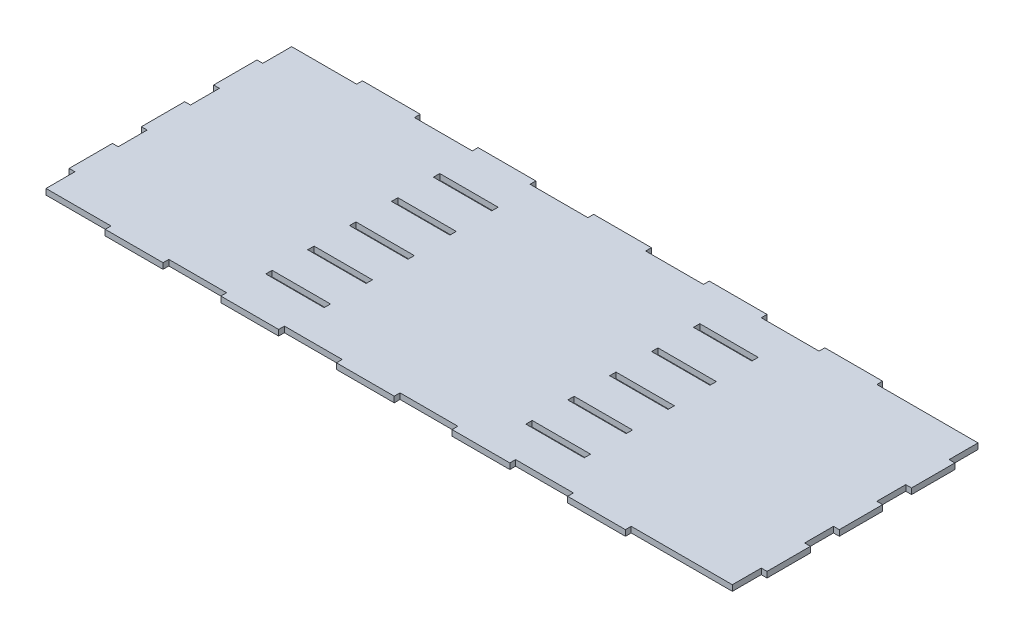
SolidWorks part; units mm, degrees
ref_plane "Спереди" through (0, 0, 0) normal (0, 0, 1) x (1, 0, 0)
ref_plane "Сверху" through (0, 0, 0) normal (0, 1, 0) x (1, 0, 0)
ref_plane "Справа" through (0, 0, 0) normal (1, 0, 0) x (0, 0, -1)
sketch "Эскиз1" plane through (0, 0, 0) normal (0, 1, 0) x (1, 0, 0)
  line L0 (0, 0) -> (0, 20)
  line L1 (0, 0) -> (475, 0) construction
  line L2 (0, 0) -> (0, 170) construction
  line L3 (0, 170) -> (475, 170) construction
  line L4 (475, 0) -> (475, 170) construction
  line L5 (0, 20) -> (-4, 20)
  line L6 (-4, 20) -> (-4, 50)
  line L7 (-4, 50) -> (0, 50)
  line L8 (0, 50) -> (0, 70)
  line L9 (0, 70) -> (-4, 70)
  line L10 (-4, 70) -> (-4, 100)
  line L11 (-4, 100) -> (0, 100)
  line L12 (0, 100) -> (0, 120)
  line L13 (0, 120) -> (-4, 120)
  line L14 (-4, 120) -> (-4, 150)
  line L15 (-4, 100) -> (-4, 120) construction
  line L16 (-4, 150) -> (0, 150)
  line L17 (0, 150) -> (0, 170)
  line L18 (-4, 50) -> (-4, 70) construction
  line L19 (0, 0) -> (45, 0)
  line L20 (45, 0) -> (45, -4)
  line L21 (45, -4) -> (85, -4)
  line L22 (85, -4) -> (85, 0)
  line L23 (85, 0) -> (125, 0)
  line L24 (125, 0) -> (125, -4)
  line L25 (125, -4) -> (165, -4)
  line L26 (165, -4) -> (165, 0)
  line L27 (165, 0) -> (205, 0)
  line L28 (205, 0) -> (205, -4)
  line L29 (205, -4) -> (245, -4)
  line L30 (245, -4) -> (245, 0)
  line L31 (245, 0) -> (285, 0)
  line L32 (285, 0) -> (285, -4)
  line L33 (285, -4) -> (325, -4)
  line L34 (325, -4) -> (325, 0)
  line L35 (325, 0) -> (365, 0)
  line L36 (365, 0) -> (365, -4)
  line L37 (365, -4) -> (405, -4)
  line L38 (405, -4) -> (405, 0)
  line L39 (405, 0) -> (475, 0)
  line L40 (365, -4) -> (325, -4) construction
  line L41 (285, -4) -> (245, -4) construction
  line L42 (205, -4) -> (165, -4) construction
  line L43 (125, -4) -> (85, -4) construction
  line L44 (385, -4) -> (385, 10.5697) construction
  line L45 (65, -4) -> (65, 14.3364) construction
  line L46 (145, -4) -> (145, 17.1826) construction
  line L47 (225, -4) -> (225, 12.9765) construction
  line L48 (305, -4) -> (305, 12.9765) construction
  line L49 (475, 0) -> (475, 20)
  line L50 (475, 20) -> (479, 20)
  line L51 (479, 20) -> (479, 50)
  line L52 (479, 50) -> (475, 50)
  line L53 (475, 50) -> (475, 70)
  line L54 (475, 70) -> (479, 70)
  line L55 (479, 70) -> (479, 100)
  line L56 (479, 100) -> (475, 100)
  line L57 (475, 100) -> (475, 120)
  line L58 (475, 120) -> (479, 120)
  line L59 (479, 120) -> (479, 150)
  line L60 (479, 150) -> (475, 150)
  line L61 (475, 150) -> (475, 170)
  line L62 (479, 50) -> (479, 70) construction
  line L63 (479, 100) -> (479, 120) construction
  line L64 (0, 170) -> (45, 170)
  line L65 (45, 170) -> (45, 174)
  line L66 (45, 174) -> (85, 174)
  line L67 (85, 174) -> (85, 170)
  line L68 (85, 170) -> (125, 170)
  line L69 (125, 170) -> (125, 174)
  line L70 (125, 174) -> (165, 174)
  line L71 (165, 174) -> (165, 170)
  line L72 (165, 170) -> (205, 170)
  line L73 (205, 170) -> (205, 174)
  line L74 (205, 174) -> (245, 174)
  line L75 (245, 174) -> (245, 170)
  line L76 (245, 170) -> (285, 170)
  line L77 (285, 170) -> (285, 174)
  line L78 (285, 174) -> (325, 174)
  line L79 (325, 174) -> (325, 170)
  line L80 (325, 170) -> (365, 170)
  line L81 (365, 170) -> (365, 174)
  line L82 (365, 174) -> (405, 174)
  line L83 (405, 174) -> (405, 170)
  line L84 (405, 170) -> (475, 170)
  line L85 (365, 174) -> (325, 174) construction
  line L86 (285, 174) -> (245, 174) construction
  line L87 (205, 174) -> (165, 174) construction
  line L88 (125, 174) -> (85, 174) construction
  line L89 (65, 174) -> (65, 202.1698) construction
  line L90 (145, 174) -> (145, 197.0575) construction
  line L91 (225, 174) -> (225, 197.0575) construction
  line L92 (305, 174) -> (305, 192.5842) construction
  line L93 (385, 174) -> (385, 197.0575) construction
  dimension "D1" = 475
  dimension "D2" = 170
  dimension "D3" = 30
  dimension "D4" = 20
  dimension "D5" = 20
  dimension "D6" = 30
  dimension "D7" = 20
  dimension "D8" = 4
  dimension "D9" = 30
  dimension "D10" = 40
  dimension "D11" = 40
  dimension "D12" = 40
  dimension "=" = 40
  dimension "D13" = 40
  dimension "D14" = 80
  dimension "D15" = 80
  dimension "D16" = 80
  dimension "D17" = 80
  dimension "D18" = 65
  dimension "D19" = 4
  dimension "D20" = 90
  dimension "D21" = 20
  dimension "D22" = 30
  dimension "D23" = 20
  dimension "D24" = 30
  dimension "D25" = 20
  dimension "D26" = 30
  dimension "D27" = 4
  dimension "D28" = 4
  dimension "D29" = 65
  dimension "D30" = 40
  dimension "D31" = 40
  dimension "D32" = 40
  dimension "D33" = 40
  dimension "D34" = 40
extrude "Бобышка-Вытянуть1" add sketch "Эскиз1" against normal blind 4
sketch "Эскиз3" plane through (0, 0, 0) normal (0, 1, 0) x (1, 0, 0)
  line L0 (0, 20) -> (475, 20) construction
  line L1 (237.5, 20) -> (237.5, -35.7564) construction
  line L2 (167.7, 27) -> (237.5, 27) construction
  line L3 (147.5, 29.2) -> (147.5, 49.5346) construction
  line L4 (167.7, 29.2) -> (127.3, 29.2)
  line L5 (167.7, 29.2) -> (167.7, 24.8)
  line L6 (167.7, 24.8) -> (127.3, 24.8)
  line L7 (127.3, 29.2) -> (127.3, 24.8)
  line L8 (347.7, 29.2) -> (347.7, 24.8)
  line L9 (307.3, 24.8) -> (347.7, 24.8)
  line L10 (307.3, 29.2) -> (307.3, 24.8)
  line L11 (307.3, 29.2) -> (347.7, 29.2)
  line L12 (327.5, 29.2) -> (327.5, 39.6268) construction
  line L13 (85, 0) -> (125, 0) construction
  line L14 (167.7, 58.2) -> (127.3, 58.2)
  line L15 (127.3, 58.2) -> (127.3, 53.8)
  line L16 (167.7, 53.8) -> (127.3, 53.8)
  line L17 (167.7, 58.2) -> (167.7, 53.8)
  line L18 (347.7, 58.2) -> (347.7, 53.8)
  line L19 (307.3, 58.2) -> (347.7, 58.2)
  line L20 (307.3, 53.8) -> (347.7, 53.8)
  line L21 (307.3, 58.2) -> (307.3, 53.8)
  line L22 (167.7, 87.2) -> (127.3, 87.2)
  line L23 (127.3, 87.2) -> (127.3, 82.8)
  line L24 (167.7, 82.8) -> (127.3, 82.8)
  line L25 (167.7, 87.2) -> (167.7, 82.8)
  line L26 (347.7, 87.2) -> (347.7, 82.8)
  line L27 (307.3, 87.2) -> (347.7, 87.2)
  line L28 (307.3, 82.8) -> (347.7, 82.8)
  line L29 (307.3, 87.2) -> (307.3, 82.8)
  line L30 (167.7, 116.2) -> (127.3, 116.2)
  line L31 (127.3, 116.2) -> (127.3, 111.8)
  line L32 (167.7, 111.8) -> (127.3, 111.8)
  line L33 (167.7, 116.2) -> (167.7, 111.8)
  line L34 (347.7, 116.2) -> (347.7, 111.8)
  line L35 (307.3, 116.2) -> (347.7, 116.2)
  line L36 (307.3, 111.8) -> (347.7, 111.8)
  line L37 (307.3, 116.2) -> (307.3, 111.8)
  line L38 (167.7, 145.2) -> (127.3, 145.2)
  line L39 (127.3, 145.2) -> (127.3, 140.8)
  line L40 (167.7, 140.8) -> (127.3, 140.8)
  line L41 (167.7, 145.2) -> (167.7, 140.8)
  line L42 (347.7, 145.2) -> (347.7, 140.8)
  line L43 (307.3, 145.2) -> (347.7, 145.2)
  line L44 (307.3, 140.8) -> (347.7, 140.8)
  line L45 (307.3, 145.2) -> (307.3, 140.8)
  line L46 (167.7, 29.2) -> (167.7, 53.8) construction
  dimension "D1" = 40.4
  dimension "D2" = 4.4
  dimension "D3" = 180
  dimension "D4" = 24.8
  dimension "D6" = 29
  dimension "D5" = 5
extrude "Вырез-Вытянуть1" cut sketch "Эскиз3" against normal through all
